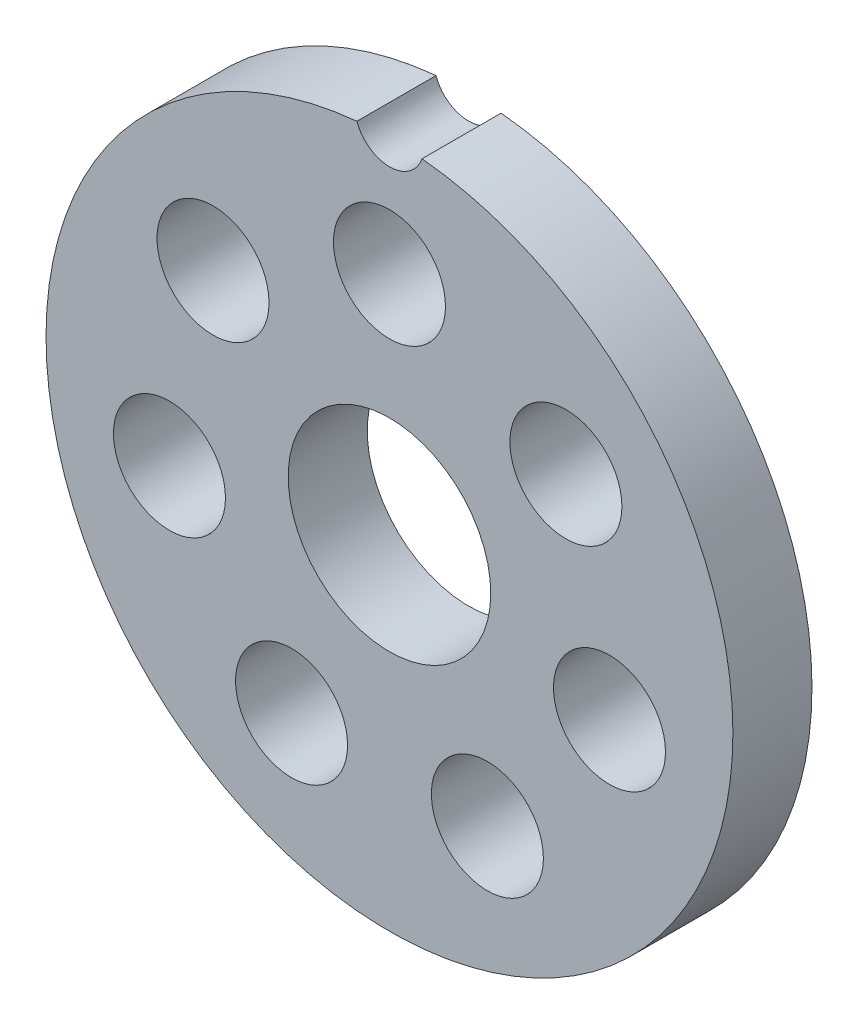
SolidWorks part; units mm, degrees
ref_plane "Front Plane" through (0, 0, 0) normal (0, 0, 1) x (1, 0, 0)
ref_plane "Top Plane" through (0, 0, 0) normal (0, 1, 0) x (1, 0, 0)
ref_plane "Right Plane" through (0, 0, 0) normal (1, 0, 0) x (0, 0, -1)
sketch "Sketch1" plane through (0, 0, 0) normal (0, 0, 1) x (1, 0, 0)
  line L0 (0, 5.2324) -> (0, 3.1242) construction
  line L1 (0, 3.1242) -> (0, 9.8298) construction
  line L2 (1.0033, 10.5442) -> (-1.0033, 10.5442) construction
  circle A0 centre (0, 0) radius 10.5918
  circle A1 centre (0, 0) radius 3.1242
  circle A2 centre (0, 6.9596) radius 1.7272
  circle A3 centre (5.4412, 4.3392) radius 1.7272
  circle A4 centre (6.7851, -1.5487) radius 1.7272
  circle A5 centre (3.0197, -6.2704) radius 1.7272
  circle A6 centre (-3.0197, -6.2704) radius 1.7272
  circle A7 centre (-6.7851, -1.5487) radius 1.7272
  circle A8 centre (-5.4412, 4.3392) radius 1.7272
  circle A9 centre (0, 0) radius 6.9596
  circle A10 centre (0, 10.8915) radius 1.0617
  point P22 (0, 0)
  point P27 (0, 0)
  point P28 (0, 0)
  point P29 (1.0464, 5.3241)
  point P30 (0, 11.3102)
  point P31 (0, 0)
  point P32 (4.4317, 3.5341)
  dimension "D1" = 7
  dimension "D2" = 2.1082
  dimension "D3" = 21.1836
  dimension "D4" = 6.2484
  dimension "D7" = 3.4544
  dimension "D5" = 6.7056
  dimension "D6" = 2.0066
extrude "Boss-Extrude1" add sketch "Sketch1" along normal blind 2.4384 contours A10 A0 A9 A4 A5 A6 A7 A8 A2 A3 | A4 A9 A3 A2 A8 A7 A6 A5 A1
